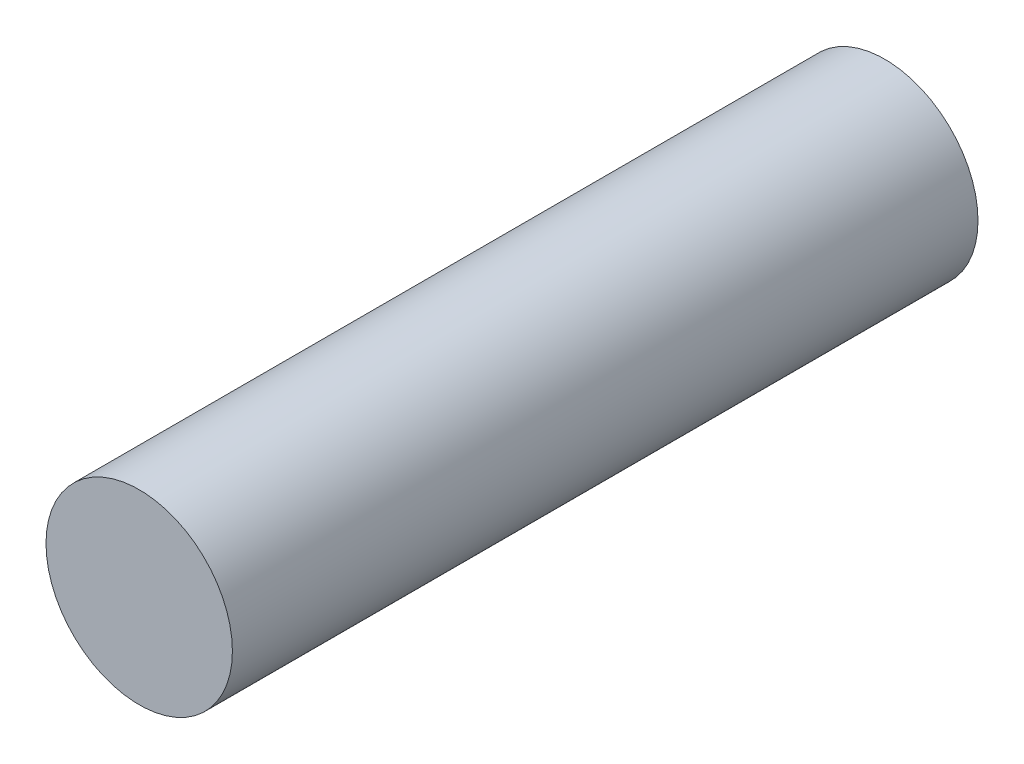
SolidWorks part; units mm, degrees
ref_plane "Front Plane" through (0, 0, 0) normal (0, 0, 1) x (1, 0, 0)
ref_plane "Top Plane" through (0, 0, 0) normal (0, 1, 0) x (1, 0, 0)
ref_plane "Right Plane" through (0, 0, 0) normal (1, 0, 0) x (0, 0, -1)
sketch "Sketch1" plane through (0, 0, 0) normal (0, 0, 1) x (1, 0, 0)
  circle A0 centre (-5.1467, 5.6335) radius 6.35
  dimension "D1" = 12.7
extrude "Boss-Extrude1" add sketch "Sketch1" along normal blind 50.8
sketch "Sketch2" plane through (0, 0, 0) normal (0, 0, -1) x (-1, 0, 0)
  circle A0 centre (5.1467, 5.6335) radius 2.0193
  circle A3 centre (5.1467, 5.6335) radius 6.35
  circle A4 centre (5.1467, 5.6335) radius 6.35
  dimension "D1" = 4.0386
  dimension "D2" = 0
extrude "Cut-Extrude3" cut sketch "Sketch2" against normal blind 19.05 contours A0
